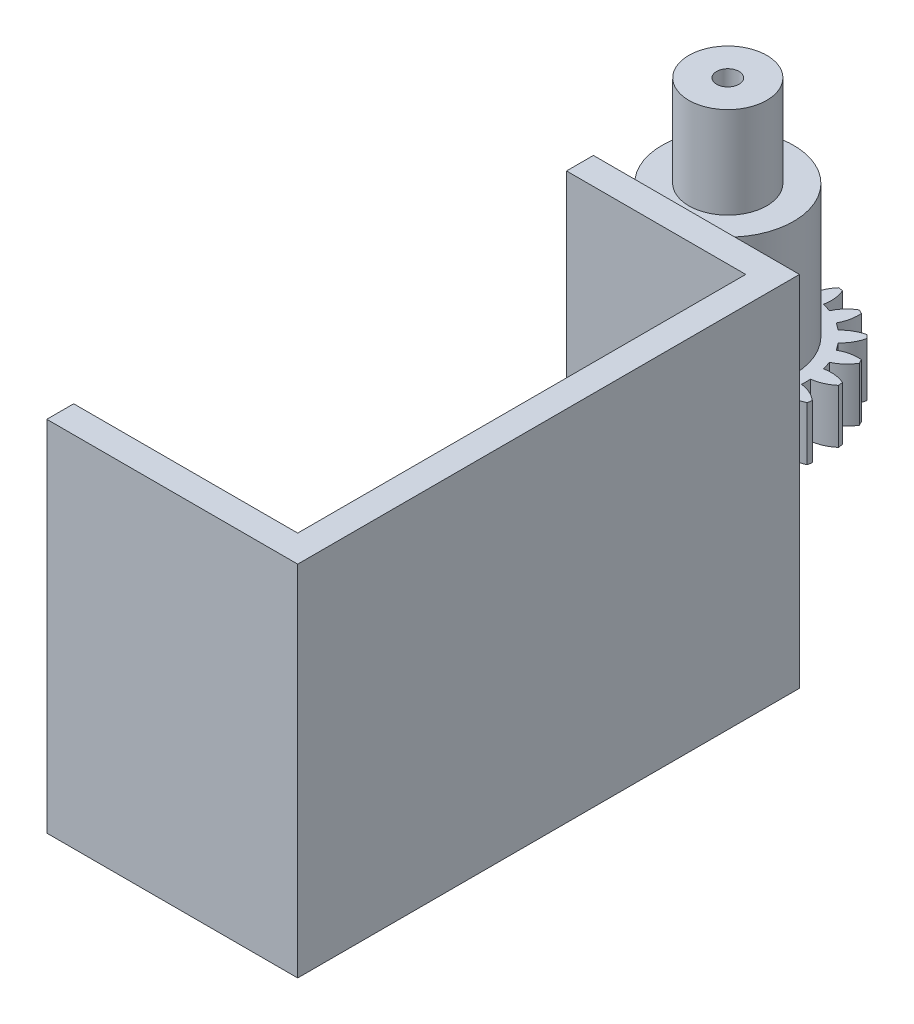
SolidWorks part; units mm, degrees
ref_plane "前视基准面" through (0, 0, 0) normal (0, 0, 1) x (1, 0, 0)
ref_plane "上视基准面" through (0, 0, 0) normal (0, 1, 0) x (1, 0, 0)
ref_plane "右视基准面" through (0, 0, 0) normal (1, 0, 0) x (0, 0, -1)
sketch "草图1" plane through (0, 0, 0) normal (0, 1, 0) x (1, 0, 0)
  line L0 (-5, 0) -> (-5, -13)
  line L10 (-5, -13) -> (15, -13)
  line L11 (15, -13) -> (15, -63)
  line L12 (15, -63) -> (-10, -63)
  line L13 (-10, -63) -> (-10, -66)
  line L14 (-10, -66) -> (18, -66)
  line L15 (18, -66) -> (18, -10)
  line L16 (18, -10) -> (5, -10)
  line L17 (5, -10) -> (5, 0)
  arc A2 (5, 0) -> (-5, 0) centre (0, 0) ccw
  arc A3 (-5, 0) -> (5, 0) centre (0, 0) ccw construction
  dimension "D1" = 10
  dimension "D2" = 3
  dimension "D3" = 3
  dimension "D4" = 3
  dimension "D5" = 50
  dimension "D6" = 10
  dimension "D7" = 25
  dimension "D8" = 10
extrude "凸台-拉伸1" add sketch "草图1" against normal blind 6
sketch "草图2" plane through (0, 0, 0) normal (0, 1, 0) x (1, 0, 0)
  line L15 (-5, -13) -> (15, -13) construction
  line L16 (18, -66) -> (18, -10) construction
  line L17 (15, -13) -> (15, -63) construction
  line L18 (-10, -66) -> (18, -66) construction
  line L19 (15, -63) -> (-10, -63) construction
  line L20 (-10, -63) -> (-10, -66) construction
  line L21 (-5, -13) -> (15, -13)
  line L22 (18, -66) -> (18, -10)
  line L23 (15, -13) -> (15, -63)
  line L24 (-10, -66) -> (18, -66)
  line L25 (15, -63) -> (-10, -63)
  line L26 (-10, -63) -> (-10, -66)
  line L27 (18, -10) -> (-5, -10)
  line L28 (-5, 0) -> (-5, -13) construction
  line L29 (-5, -10) -> (-5, -13)
extrude "凸台-拉伸2" add sketch "草图2" along normal mid plane 40
sketch "草图3" plane through (0, -20, 0) normal (0, -1, 0) x (1, 0, 0)
  line L5 (-10, 63) -> (15, 63)
  line L6 (-10, 63) -> (-10, 13)
  line L7 (-10, 13) -> (15, 13)
  line L8 (15, 63) -> (15, 13)
extrude "凸台-拉伸3" add sketch "草图3" against normal blind 3
sketch "草图4" plane through (0, -6, 0) normal (0, -1, 0) x (1, 0, 0)
  arc A80 (-0.5047, 8.7344) -> (-1.471, 10.9012) centre (-4.4767, 8.262) ccw
  arc A81 (-1.471, 10.9012) -> (-1.9816, 10.82) centre (0, 0) ccw
  arc A82 (-1.9816, 10.82) -> (-2.2284, 8.4605) centre (1.6943, 9.2429) ccw
  arc A83 (-2.2284, 8.4605) -> (-3.1791, 8.151) centre (0, 0) ccw
  arc A84 (-3.1791, 8.151) -> (-4.7676, 9.9131) centre (-6.8107, 6.4743) ccw
  arc A85 (-4.7676, 9.9131) -> (-5.2282, 9.6781) centre (0, 0) ccw
  arc A86 (-5.2282, 9.6781) -> (-4.7337, 7.3578) centre (-1.2448, 9.3141) ccw
  arc A87 (-4.7337, 7.3578) -> (-5.5423, 6.7696) centre (0, 0) ccw
  arc A88 (-5.5423, 6.7696) -> (-7.5976, 7.9547) centre (-8.4781, 4.0528) ccw
  arc A89 (-7.5976, 7.9547) -> (-7.963, 7.5888) centre (0, 0) ccw
  arc A90 (-7.963, 7.5888) -> (-6.7757, 5.5348) centre (-4.0621, 8.4736) ccw
  arc A91 (-6.7757, 5.5348) -> (-7.363, 4.7256) centre (0, 0) ccw
  arc A92 (-7.363, 4.7256) -> (-9.6839, 5.2175) centre (-9.3155, 1.2345) ccw
  arc A93 (-9.6839, 5.2175) -> (-9.9184, 4.7567) centre (0, 0) ccw
  arc A94 (-9.9184, 4.7567) -> (-8.1545, 3.1701) centre (-6.4818, 6.8036) ccw
  arc A95 (-8.1545, 3.1701) -> (-8.4629, 2.2191) centre (0, 0) ccw
  arc A96 (-8.4629, 2.2191) -> (-10.8222, 1.9697) centre (-9.241, -1.7045) ccw
  arc A97 (-10.8222, 1.9697) -> (-10.9028, 1.459) centre (0, 0) ccw
  arc A98 (-10.9028, 1.459) -> (-8.735, 0.4951) centre (-8.2669, 4.4676) ccw
  arc A99 (-8.735, 0.4951) -> (-8.7344, -0.5047) centre (0, 0) ccw
  arc A100 (-8.7344, -0.5047) -> (-10.9012, -1.471) centre (-8.262, -4.4767) ccw
  arc A101 (-10.9012, -1.471) -> (-10.82, -1.9816) centre (0, 0) ccw
  arc A102 (-10.82, -1.9816) -> (-8.4605, -2.2284) centre (-9.2429, 1.6943) ccw
  arc A103 (-8.4605, -2.2284) -> (-8.151, -3.1791) centre (0, 0) ccw
  arc A104 (-8.151, -3.1791) -> (-9.9131, -4.7676) centre (-6.4743, -6.8107) ccw
  arc A105 (-9.9131, -4.7676) -> (-9.6781, -5.2282) centre (0, 0) ccw
  arc A106 (-9.6781, -5.2282) -> (-7.3578, -4.7337) centre (-9.3141, -1.2448) ccw
  arc A107 (-7.3578, -4.7337) -> (-6.7696, -5.5423) centre (0, 0) ccw
  arc A108 (-6.7696, -5.5423) -> (-7.9547, -7.5976) centre (-4.0528, -8.4781) ccw
  arc A109 (-7.9547, -7.5976) -> (-7.5888, -7.963) centre (0, 0) ccw
  arc A110 (-7.5888, -7.963) -> (-5.5348, -6.7757) centre (-8.4736, -4.0621) ccw
  arc A111 (-5.5348, -6.7757) -> (-4.7256, -7.363) centre (0, 0) ccw
  arc A112 (-4.7256, -7.363) -> (-5.2175, -9.6839) centre (-1.2345, -9.3155) ccw
  arc A113 (-5.2175, -9.6839) -> (-4.7567, -9.9184) centre (0, 0) ccw
  arc A114 (-4.7567, -9.9184) -> (-3.1701, -8.1545) centre (-6.8036, -6.4818) ccw
  arc A115 (-3.1701, -8.1545) -> (-2.2191, -8.4629) centre (0, 0) ccw
  arc A116 (-2.2191, -8.4629) -> (-1.9697, -10.8222) centre (1.7045, -9.241) ccw
  arc A117 (-1.9697, -10.8222) -> (-1.459, -10.9028) centre (0, 0) ccw
  arc A118 (-1.459, -10.9028) -> (-0.4951, -8.735) centre (-4.4676, -8.2669) ccw
  arc A119 (-0.4951, -8.735) -> (0.5047, -8.7344) centre (0, 0) ccw
  arc A120 (0.5047, -8.7344) -> (1.471, -10.9012) centre (4.4767, -8.262) ccw
  arc A121 (1.471, -10.9012) -> (1.9816, -10.82) centre (0, 0) ccw
  arc A122 (1.9816, -10.82) -> (2.2284, -8.4605) centre (-1.6943, -9.2429) ccw
  arc A123 (2.2284, -8.4605) -> (3.1791, -8.151) centre (0, 0) ccw
  arc A124 (3.1791, -8.151) -> (4.7676, -9.9131) centre (6.8107, -6.4743) ccw
  arc A125 (4.7676, -9.9131) -> (5.2282, -9.6781) centre (0, 0) ccw
  arc A126 (5.2282, -9.6781) -> (4.7337, -7.3578) centre (1.2448, -9.3141) ccw
  arc A127 (4.7337, -7.3578) -> (5.5423, -6.7696) centre (0, 0) ccw
  arc A128 (5.5423, -6.7696) -> (7.5976, -7.9547) centre (8.4781, -4.0528) ccw
  arc A129 (7.5976, -7.9547) -> (7.963, -7.5888) centre (0, 0) ccw
  arc A130 (7.963, -7.5888) -> (6.7757, -5.5348) centre (4.0621, -8.4736) ccw
  arc A131 (6.7757, -5.5348) -> (7.363, -4.7256) centre (0, 0) ccw
  arc A132 (7.363, -4.7256) -> (9.6839, -5.2175) centre (9.3155, -1.2345) ccw
  arc A133 (9.6839, -5.2175) -> (9.9184, -4.7567) centre (0, 0) ccw
  arc A134 (9.9184, -4.7567) -> (8.1545, -3.1701) centre (6.4818, -6.8036) ccw
  arc A135 (8.1545, -3.1701) -> (8.4629, -2.2191) centre (0, 0) ccw
  arc A136 (8.4629, -2.2191) -> (10.8222, -1.9697) centre (9.241, 1.7045) ccw
  arc A137 (10.8222, -1.9697) -> (10.9028, -1.459) centre (0, 0) ccw
  arc A138 (10.9028, -1.459) -> (8.735, -0.4951) centre (8.2669, -4.4676) ccw
  arc A139 (8.735, -0.4951) -> (8.7344, 0.5047) centre (0, 0) ccw
  arc A140 (8.7344, 0.5047) -> (10.9012, 1.471) centre (8.262, 4.4767) ccw
  arc A141 (10.9012, 1.471) -> (10.82, 1.9816) centre (0, 0) ccw
  arc A142 (10.82, 1.9816) -> (8.4605, 2.2284) centre (9.2429, -1.6943) ccw
  arc A143 (8.4605, 2.2284) -> (8.151, 3.1791) centre (0, 0) ccw
  arc A144 (8.151, 3.1791) -> (9.9131, 4.7676) centre (6.4743, 6.8107) ccw
  arc A145 (9.9131, 4.7676) -> (9.6781, 5.2282) centre (0, 0) ccw
  arc A146 (9.6781, 5.2282) -> (7.3578, 4.7337) centre (9.3141, 1.2448) ccw
  arc A147 (7.3578, 4.7337) -> (6.7696, 5.5423) centre (0, 0) ccw
  arc A148 (6.7696, 5.5423) -> (7.9547, 7.5976) centre (4.0528, 8.4781) ccw
  arc A149 (7.9547, 7.5976) -> (7.5888, 7.963) centre (0, 0) ccw
  arc A150 (7.5888, 7.963) -> (5.5348, 6.7757) centre (8.4736, 4.0621) ccw
  arc A151 (5.5348, 6.7757) -> (4.7256, 7.363) centre (0, 0) ccw
  arc A152 (4.7256, 7.363) -> (5.2175, 9.6839) centre (1.2345, 9.3155) ccw
  arc A153 (5.2175, 9.6839) -> (4.7567, 9.9184) centre (0, 0) ccw
  arc A154 (4.7567, 9.9184) -> (3.1701, 8.1545) centre (6.8036, 6.4818) ccw
  arc A155 (3.1701, 8.1545) -> (2.2191, 8.4629) centre (0, 0) ccw
  arc A156 (2.2191, 8.4629) -> (1.9697, 10.8222) centre (-1.7045, 9.241) ccw
  arc A157 (1.9697, 10.8222) -> (1.459, 10.9028) centre (0, 0) ccw
  arc A158 (1.459, 10.9028) -> (0.4951, 8.735) centre (4.4676, 8.2669) ccw
  arc A159 (0.4951, 8.735) -> (-0.5047, 8.7344) centre (0, 0) ccw
  arc A160 (-0.5047, 8.7344) -> (-1.471, 10.9012) centre (-4.4767, 8.262) ccw
  arc A161 (-1.471, 10.9012) -> (-1.9816, 10.82) centre (0, 0) ccw
  arc A162 (-1.9816, 10.82) -> (-2.2284, 8.4605) centre (1.6943, 9.2429) ccw
  arc A163 (-2.2284, 8.4605) -> (-3.1791, 8.151) centre (0, 0) ccw
  arc A164 (-3.1791, 8.151) -> (-4.7676, 9.9131) centre (-6.8107, 6.4743) ccw
  arc A165 (-4.7676, 9.9131) -> (-5.2282, 9.6781) centre (0, 0) ccw
  arc A166 (-5.2282, 9.6781) -> (-4.7337, 7.3578) centre (-1.2448, 9.3141) ccw
  arc A167 (-4.7337, 7.3578) -> (-5.5423, 6.7696) centre (0, 0) ccw
  arc A168 (-5.5423, 6.7696) -> (-7.5976, 7.9547) centre (-8.4781, 4.0528) ccw
  arc A169 (-7.5976, 7.9547) -> (-7.963, 7.5888) centre (0, 0) ccw
  arc A170 (-7.963, 7.5888) -> (-6.7757, 5.5348) centre (-4.0621, 8.4736) ccw
  arc A171 (-6.7757, 5.5348) -> (-7.363, 4.7256) centre (0, 0) ccw
  arc A172 (-7.363, 4.7256) -> (-9.6839, 5.2175) centre (-9.3155, 1.2345) ccw
  arc A173 (-9.6839, 5.2175) -> (-9.9184, 4.7567) centre (0, 0) ccw
  arc A174 (-9.9184, 4.7567) -> (-8.1545, 3.1701) centre (-6.4818, 6.8036) ccw
  arc A175 (-8.1545, 3.1701) -> (-8.4629, 2.2191) centre (0, 0) ccw
  arc A176 (-8.4629, 2.2191) -> (-10.8222, 1.9697) centre (-9.241, -1.7045) ccw
  arc A177 (-10.8222, 1.9697) -> (-10.9028, 1.459) centre (0, 0) ccw
  arc A178 (-10.9028, 1.459) -> (-8.735, 0.4951) centre (-8.2669, 4.4676) ccw
  arc A179 (-8.735, 0.4951) -> (-8.7344, -0.5047) centre (0, 0) ccw
  arc A180 (-8.7344, -0.5047) -> (-10.9012, -1.471) centre (-8.262, -4.4767) ccw
  arc A181 (-10.9012, -1.471) -> (-10.82, -1.9816) centre (0, 0) ccw
  arc A182 (-10.82, -1.9816) -> (-8.4605, -2.2284) centre (-9.2429, 1.6943) ccw
  arc A183 (-8.4605, -2.2284) -> (-8.151, -3.1791) centre (0, 0) ccw
  arc A184 (-8.151, -3.1791) -> (-9.9131, -4.7676) centre (-6.4743, -6.8107) ccw
  arc A185 (-9.9131, -4.7676) -> (-9.6781, -5.2282) centre (0, 0) ccw
  arc A186 (-9.6781, -5.2282) -> (-7.3578, -4.7337) centre (-9.3141, -1.2448) ccw
  arc A187 (-7.3578, -4.7337) -> (-6.7696, -5.5423) centre (0, 0) ccw
  arc A188 (-6.7696, -5.5423) -> (-7.9547, -7.5976) centre (-4.0528, -8.4781) ccw
  arc A189 (-7.9547, -7.5976) -> (-7.5888, -7.963) centre (0, 0) ccw
  arc A190 (-7.5888, -7.963) -> (-5.5348, -6.7757) centre (-8.4736, -4.0621) ccw
  arc A191 (-5.5348, -6.7757) -> (-4.7256, -7.363) centre (0, 0) ccw
  arc A192 (-4.7256, -7.363) -> (-5.2175, -9.6839) centre (-1.2345, -9.3155) ccw
  arc A193 (-5.2175, -9.6839) -> (-4.7567, -9.9184) centre (0, 0) ccw
  arc A194 (-4.7567, -9.9184) -> (-3.1701, -8.1545) centre (-6.8036, -6.4818) ccw
  arc A195 (-3.1701, -8.1545) -> (-2.2191, -8.4629) centre (0, 0) ccw
  arc A196 (-2.2191, -8.4629) -> (-1.9697, -10.8222) centre (1.7045, -9.241) ccw
  arc A197 (-1.9697, -10.8222) -> (-1.459, -10.9028) centre (0, 0) ccw
  arc A198 (-1.459, -10.9028) -> (-0.4951, -8.735) centre (-4.4676, -8.2669) ccw
  arc A199 (-0.4951, -8.735) -> (0.5047, -8.7344) centre (0, 0) ccw
  arc A200 (0.5047, -8.7344) -> (1.471, -10.9012) centre (4.4767, -8.262) ccw
  arc A201 (1.471, -10.9012) -> (1.9816, -10.82) centre (0, 0) ccw
  arc A202 (1.9816, -10.82) -> (2.2284, -8.4605) centre (-1.6943, -9.2429) ccw
  arc A203 (2.2284, -8.4605) -> (3.1791, -8.151) centre (0, 0) ccw
  arc A204 (3.1791, -8.151) -> (4.7676, -9.9131) centre (6.8107, -6.4743) ccw
  arc A205 (4.7676, -9.9131) -> (5.2282, -9.6781) centre (0, 0) ccw
  arc A206 (5.2282, -9.6781) -> (4.7337, -7.3578) centre (1.2448, -9.3141) ccw
  arc A207 (4.7337, -7.3578) -> (5.5423, -6.7696) centre (0, 0) ccw
  arc A208 (5.5423, -6.7696) -> (7.5976, -7.9547) centre (8.4781, -4.0528) ccw
  arc A209 (7.5976, -7.9547) -> (7.963, -7.5888) centre (0, 0) ccw
  arc A210 (7.963, -7.5888) -> (6.7757, -5.5348) centre (4.0621, -8.4736) ccw
  arc A211 (6.7757, -5.5348) -> (7.363, -4.7256) centre (0, 0) ccw
  arc A212 (7.363, -4.7256) -> (9.6839, -5.2175) centre (9.3155, -1.2345) ccw
  arc A213 (9.6839, -5.2175) -> (9.9184, -4.7567) centre (0, 0) ccw
  arc A214 (9.9184, -4.7567) -> (8.1545, -3.1701) centre (6.4818, -6.8036) ccw
  arc A215 (8.1545, -3.1701) -> (8.4629, -2.2191) centre (0, 0) ccw
  arc A216 (8.4629, -2.2191) -> (10.8222, -1.9697) centre (9.241, 1.7045) ccw
  arc A217 (10.8222, -1.9697) -> (10.9028, -1.459) centre (0, 0) ccw
  arc A218 (10.9028, -1.459) -> (8.735, -0.4951) centre (8.2669, -4.4676) ccw
  arc A219 (8.735, -0.4951) -> (8.7344, 0.5047) centre (0, 0) ccw
  arc A220 (8.7344, 0.5047) -> (10.9012, 1.471) centre (8.262, 4.4767) ccw
  arc A221 (10.9012, 1.471) -> (10.82, 1.9816) centre (0, 0) ccw
  arc A222 (10.82, 1.9816) -> (8.4605, 2.2284) centre (9.2429, -1.6943) ccw
  arc A223 (8.4605, 2.2284) -> (8.151, 3.1791) centre (0, 0) ccw
  arc A224 (8.151, 3.1791) -> (9.9131, 4.7676) centre (6.4743, 6.8107) ccw
  arc A225 (9.9131, 4.7676) -> (9.6781, 5.2282) centre (0, 0) ccw
  arc A226 (9.6781, 5.2282) -> (7.3578, 4.7337) centre (9.3141, 1.2448) ccw
  arc A227 (7.3578, 4.7337) -> (6.7696, 5.5423) centre (0, 0) ccw
  arc A228 (6.7696, 5.5423) -> (7.9547, 7.5976) centre (4.0528, 8.4781) ccw
  arc A229 (7.9547, 7.5976) -> (7.5888, 7.963) centre (0, 0) ccw
  arc A230 (7.5888, 7.963) -> (5.5348, 6.7757) centre (8.4736, 4.0621) ccw
  arc A231 (5.5348, 6.7757) -> (4.7256, 7.363) centre (0, 0) ccw
  arc A232 (4.7256, 7.363) -> (5.2175, 9.6839) centre (1.2345, 9.3155) ccw
  arc A233 (5.2175, 9.6839) -> (4.7567, 9.9184) centre (0, 0) ccw
  arc A234 (4.7567, 9.9184) -> (3.1701, 8.1545) centre (6.8036, 6.4818) ccw
  arc A235 (3.1701, 8.1545) -> (2.2191, 8.4629) centre (0, 0) ccw
  arc A236 (2.2191, 8.4629) -> (1.9697, 10.8222) centre (-1.7045, 9.241) ccw
  arc A237 (1.9697, 10.8222) -> (1.459, 10.9028) centre (0, 0) ccw
  arc A238 (1.459, 10.9028) -> (0.4951, 8.735) centre (4.4676, 8.2669) ccw
  arc A239 (0.4951, 8.735) -> (-0.5047, 8.7344) centre (0, 0) ccw
  point P0 (0, 0)
  dimension "D1" = 0
extrude "凸台-拉伸4" add sketch "草图4" against normal blind 6
sketch "草图5" plane through (0, 0, 0) normal (0, 1, 0) x (1, 0, 0)
  circle A0 centre (0, 0) radius 7.35
  dimension "D1" = 14.7
extrude "凸台-拉伸5" add sketch "草图5" along normal blind 14.8
sketch "草图6" plane through (0, 14.8, 0) normal (0, 1, 0) x (1, 0, 0)
  circle A0 centre (0, 0) radius 4.35
  circle A1 centre (0, 0) radius 1.25
  dimension "D1" = 8.7
  dimension "D2" = 2.5
extrude "凸台-拉伸6" add sketch "草图6" along normal blind 10.2
